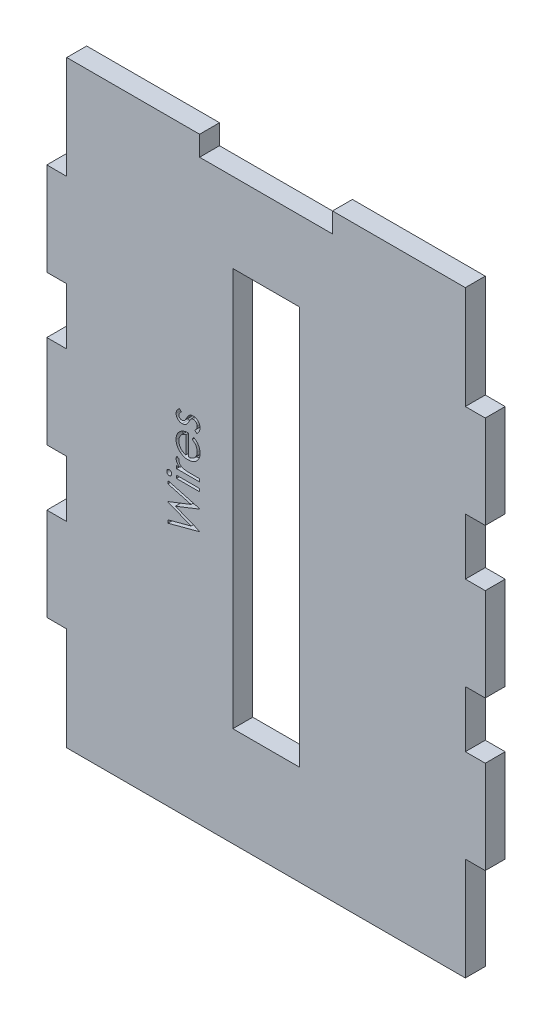
SolidWorks part; units mm, degrees
material "ABS"
ref_plane "Plan de face" through (0, 0, 0) normal (0, 0, 1) x (1, 0, 0)
ref_plane "Plan de dessus" through (0, 0, 0) normal (0, 1, 0) x (1, 0, 0)
ref_plane "Plan de droite" through (0, 0, 0) normal (1, 0, 0) x (0, 0, -1)
sketch "Esquisse1" plane through (0, 0, 0) normal (0, 0, 1) x (1, 0, 0)
  line L0 (-30, 0) -> (30, 0) construction
  line L1 (30, -45) -> (-30, -45)
  line L2 (30, -45) -> (30, 45)
  line L3 (30, 45) -> (-30, 45)
  line L4 (-30, -45) -> (-30, 45)
  line L5 (30, -45) -> (-30, 45) construction
  line L6 (30, 45) -> (-30, -45) construction
  line L7 (-30, 22.5) -> (30, 22.5) construction
  line L8 (-30, -22.5) -> (30, -22.5) construction
  line L10 (-27, -7) -> (-33, -7)
  line L11 (-27, -7) -> (-27, 7)
  line L12 (-27, 7) -> (-33, 7)
  line L13 (-33, -7) -> (-33, 7)
  line L14 (-27, -7) -> (-33, 7) construction
  line L15 (-27, 7) -> (-33, -7) construction
  line L16 (-27, 15.5) -> (-33, 15.5)
  line L17 (-27, 15.5) -> (-27, 29.5)
  line L18 (-27, 29.5) -> (-33, 29.5)
  line L19 (-33, 15.5) -> (-33, 29.5)
  line L20 (-27, 15.5) -> (-33, 29.5) construction
  line L21 (-27, 29.5) -> (-33, 15.5) construction
  line L22 (27, 15.5) -> (33, 15.5)
  line L23 (27, 15.5) -> (27, 29.5)
  line L24 (27, 29.5) -> (33, 29.5)
  line L25 (33, 15.5) -> (33, 29.5)
  line L26 (27, 15.5) -> (33, 29.5) construction
  line L27 (27, 29.5) -> (33, 15.5) construction
  line L28 (27, -7) -> (33, -7)
  line L29 (27, -7) -> (27, 7)
  line L30 (27, 7) -> (33, 7)
  line L31 (33, -7) -> (33, 7)
  line L32 (27, -7) -> (33, 7) construction
  line L33 (27, 7) -> (33, -7) construction
  line L34 (27, -29.5) -> (33, -29.5)
  line L35 (27, -29.5) -> (27, -15.5)
  line L36 (27, -15.5) -> (33, -15.5)
  line L37 (33, -29.5) -> (33, -15.5)
  line L38 (27, -29.5) -> (33, -15.5) construction
  line L39 (27, -15.5) -> (33, -29.5) construction
  line L40 (-27, -29.5) -> (-33, -29.5)
  line L41 (-27, -29.5) -> (-27, -15.5)
  line L42 (-27, -15.5) -> (-33, -15.5)
  line L43 (-33, -29.5) -> (-33, -15.5)
  line L44 (-27, -29.5) -> (-33, -15.5) construction
  line L45 (-27, -15.5) -> (-33, -29.5) construction
  point P0 (0, 0)
  dimension "D1" = 60
  dimension "D2" = 90
  dimension "D3" = 45
  dimension "D4" = 22.5
  dimension "D5" = 6
  dimension "D6" = 14
extrude "Boss.-Extru.1" add sketch "Esquisse1" along normal blind 3 contours L42 L41 L40 L4 L1 L2 L34 L35 L36 L28 L29 L30 L22 L23 L24 L3 L18 L17 L16 L12 L11 L10 | L22 L25 L24 L2 | L28 L31 L30 L2 | L34 L37 L36 L2 | L19 L16 L4 L18 | L13 L10 L4 L12 | L43 L40 L4 L42
sketch "Esquisse2" plane through (0, 0, 3) normal (0, 0, 1) x (1, 0, 0)
  line L1 (5, -30) -> (-5, -30)
  line L2 (5, -30) -> (5, 30)
  line L3 (5, 30) -> (-5, 30)
  line L4 (-5, -30) -> (-5, 30)
  line L5 (5, -30) -> (-5, 30) construction
  line L6 (5, 30) -> (-5, -30) construction
  point P0 (0, 0)
  dimension "D1" = 10
  dimension "D2" = 60
extrude "Enlèv. mat.-Extru.1" cut sketch "Esquisse2" against normal blind 10
sketch "Esquisse3" plane through (0, 0, 3) normal (0, 0, 1) x (1, 0, 0)
  line L0 (30, 45) -> (-30, 45) construction
  line L1 (10, 48) -> (-10, 48)
  line L2 (10, 48) -> (10, 42)
  line L3 (10, 42) -> (-10, 42)
  line L4 (-10, 48) -> (-10, 42)
  line L5 (10, 48) -> (-10, 42) construction
  line L6 (10, 42) -> (-10, 48) construction
  point P0 (0, 45)
  dimension "D1" = 20
  dimension "D2" = 6
extrude "Enlèv. mat.-Extru.2" cut sketch "Esquisse3" against normal blind 10
sketch "Esquisse4" plane through (0, 0, 3) normal (0, 0, 1) x (1, 0, 0)
  line L0 (-10, 20) -> (-10, -20) construction
  text T0 "Wires\r\n" font "Century Gothic" height in points 18
  point P2 (-15.149, 23.9554)
  point P3 (-10, 0)
  dimension "D1" = 10
  dimension "D2" = 40
extrude "Enlèv. mat.-Extru.3" cut sketch "Esquisse4" against normal blind 1
